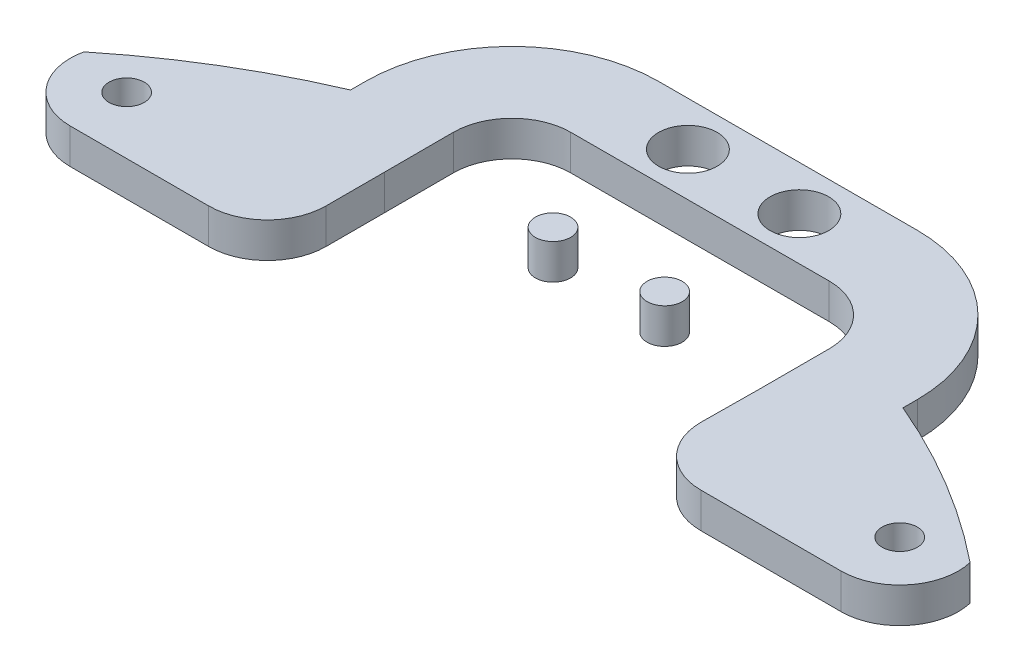
SolidWorks part; units mm, degrees
ref_plane "Alzado" through (0, 0, 0) normal (0, 0, 1) x (1, 0, 0)
ref_plane "Planta" through (0, 0, 0) normal (0, 1, 0) x (1, 0, 0)
ref_plane "Vista lateral" through (0, 0, 0) normal (1, 0, 0) x (0, 0, -1)
sketch "Croquis1" plane through (0, 0, 0) normal (0, 1, 0) x (1, 0, 0)
  line L0 (28.7017, 0) -> (94.4017, 0) construction
  line L5 (77.4951, 5) -> (77.4499, 0.0456)
  line L6 (45.5034, 5) -> (45.5034, 0)
  line L7 (84.9939, 9.6814) -> (84.9936, 10.9216)
  line L9 (94.4017, 0) -> (28.7017, 0) construction
  line L10 (94.4017, -5) -> (82.4497, -5)
  line L11 (72.4729, 23.4008) -> (50.4729, 23.3643)
  line L12 (37.9937, 10.8436) -> (37.994, 9.602)
  line L13 (40.5034, -5) -> (28.7017, -5)
  line L20 (77.4951, 5) -> (77.4936, 10.9091)
  line L21 (45.4937, 10.8561) -> (45.5302, -11.1439)
  line L22 (72.4853, 15.9008) -> (50.4854, 15.8643)
  line L23 (77.5301, -11.0908) -> (77.4936, 10.9091)
  line L24 (50.5384, -16.1356) -> (72.5384, -16.0991)
  line L25 (45.4937, 10.8561) -> (45.5034, 5)
  line L26 (72.4853, 15.9008) -> (50.4854, 15.8643)
  arc A2 (121.1732, -38.5278) -> (1.9783, -38.7255) centre (61.5873, -45.5647) ccw construction
  arc A3 (99.2741, 1.1226) -> (84.9939, 9.6814) centre (61.5873, -45.5647) ccw
  arc A4 (37.994, 9.602) -> (23.8138, 1.0525) centre (61.5873, -45.5647) ccw
  arc A5 (82.4497, -5) -> (77.4499, 0.0456) centre (82.4497, 0) cw
  arc A6 (45.5034, 0) -> (40.5034, -5) centre (40.5034, 0) cw
  arc A7 (94.4017, -5) -> (99.2741, 1.1226) centre (94.4017, 0) ccw
  arc A8 (23.8138, 1.0525) -> (28.7017, -5) centre (28.7017, 0) ccw
  arc A9 (84.9936, 10.9216) -> (72.4729, 23.4008) centre (72.4936, 10.9008) ccw
  arc A10 (50.4729, 23.3643) -> (37.9937, 10.8436) centre (50.4937, 10.8643) ccw
  circle A11 centre (56.7483, 8.102) radius 1.5 construction
  circle A12 centre (56.7483, 8.102) radius 1.5
  circle A13 centre (66.2482, 8.1177) radius 1.5 construction
  circle A14 centre (66.2482, 8.1177) radius 1.5
  circle A15 centre (56.7483, 19.5998) radius 2.5
  circle A16 centre (66.2482, 19.5998) radius 2.5
  circle A17 centre (28.6198, -0.1091) radius 1.5 construction
  circle A18 centre (94.4017, 0) radius 1.5 construction
  arc A19 (45.5302, -11.1439) -> (50.5384, -16.1356) centre (50.5302, -11.1356) ccw
  arc A20 (50.4854, 15.8643) -> (45.4937, 10.8561) centre (50.4937, 10.8643) ccw
  arc A21 (77.4936, 10.9091) -> (72.4853, 15.9008) centre (72.4936, 10.9008) ccw
  arc A22 (72.5384, -16.0991) -> (77.5301, -11.0908) centre (72.5301, -11.0991) ccw
  arc A24 (50.4854, 15.8643) -> (45.4937, 10.8561) centre (50.4937, 10.8643) ccw
  arc A25 (77.4936, 10.9091) -> (72.4853, 15.9008) centre (72.4936, 10.9008) ccw
  circle A27 centre (28.6198, -0.1091) radius 1.5
  circle A28 centre (94.4017, 0) radius 1.5
  point P3 (61.5517, 0)
  point P8 (61.5517, 0)
  point P14 (47.9937, 10.8602)
  point P16 (75.0301, -11.095)
  point P17 (48.0302, -11.1398)
  point P18 (74.9936, 10.905)
  point P29 (38.0302, -11.1564)
  point P32 (45.5034, -5)
  dimension "D1" = 7.5
  dimension "D2" = 5
  dimension "D4" = 12.5
  dimension "D5" = 12.5
  dimension "D8" = 5
  dimension "D9" = 5
  dimension "D10" = 5
  dimension "D6" = 7.5
  dimension "D7" = 7.5
  dimension "D3" = 2.5
extrude "Saliente-Extruir1" add sketch "Croquis1" along normal blind 3
